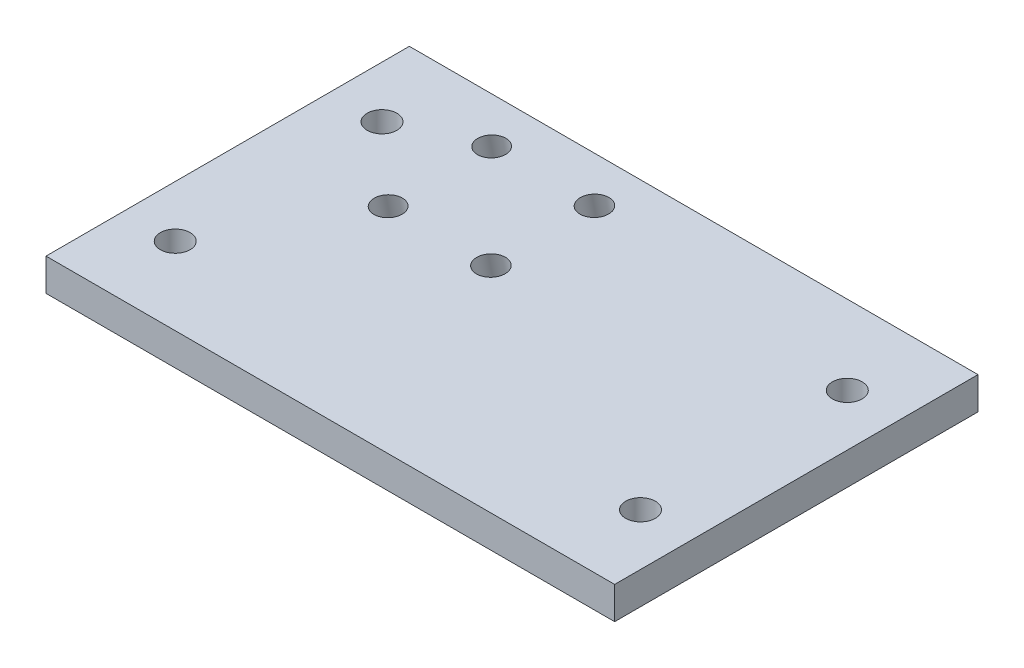
SolidWorks part; units mm, degrees
ref_plane "Front" through (0, 0, 0) normal (0, 0, 1) x (1, 0, 0)
ref_plane "Top" through (0, 0, 0) normal (0, 1, 0) x (1, 0, 0)
ref_plane "Right" through (0, 0, 0) normal (1, 0, 0) x (0, 0, -1)
sketch "Sketch1" plane through (0, 0, 0) normal (0, 1, 0) x (1, 0, 0)
  line L1 (0, 0) -> (90, 0)
  line L2 (0, 0) -> (0, 56.23)
  line L3 (0, 56.23) -> (90, 56.23)
  line L4 (90, 0) -> (90, 56.23)
  dimension "D1" = 90
  dimension "D2" = 56.23
extrude "Boss-Extrude1" add sketch "Sketch1" along normal blind 5
sketch "Sketch2" plane through (0, 5, 0) normal (0, 1, 0) x (1, 0, 0)
  circle A0 centre (82, 12) radius 2.3
  circle A1 centre (10, 12) radius 2.3
extrude "Cut-Extrude1" cut sketch "Sketch2" against normal blind 15
sketch "Sketch4" plane through (0, 5, 0) normal (0, 1, 0) x (1, 0, 0)
  circle A0 centre (39.2121, 27.5705) radius 2.2
  circle A1 centre (23.8176, 32.2728) radius 2.2
  circle A2 centre (43.572, 44.174) radius 2.2
  circle A3 centre (28.1775, 48.8763) radius 2.2
ref_plane "Plane1" through (0, 4.818, 0.9365) normal (0, 0.9816, 0.1908) x (1, 0, 0)
sketch "Sketch6" plane through (0, 4.818, 0.9365) normal (0, 0.9816, 0.1908) x (1, 0, 0)
  circle A0 centre (28.1775, 48.9324) radius 2.0398
  circle A1 centre (23.8176, 32.6339) radius 2.0398
  circle A2 centre (39.2121, 28.018) radius 2.0398
  circle A3 centre (43.572, 44.3165) radius 2.0398
sketch "Sketch7" plane through (0, 5, 0) normal (0, 1, 0) x (1, 0, 0)
  circle A0 centre (82, 44) radius 2.3
  circle A1 centre (10, 44) radius 2.3
extrude "Cut-Extrude3" cut sketch "Sketch7" against normal blind 45
sketch "Sketch8" plane through (0, 0, 0) normal (-1, 0, 0) x (0, 0, 1)
  circle A0 centre (-29.8532, 2.0033) radius 1.2661
sketch "Sketch9" plane through (0, 0, 0) normal (-1, 0, 0) x (0, 0, 1)
  line L1 (-56.23, 0) -> (4.9539, 0)
  line L2 (-56.23, 0) -> (-56.23, 5.0439)
  line L3 (-56.23, 5.0439) -> (4.9539, 5.0439)
  line L4 (4.9539, 0) -> (4.9539, 5.0439)
extrude "Cut-Extrude4" cut sketch "Sketch9" against normal blind 2
sketch "Sketch10" plane through (0, 0, 0) normal (0, -1, 0) x (-1, 0, 0)
  circle A0 centre (-21.7903, 34.1259) radius 2.2
  circle A1 centre (-37.7005, 34.1259) radius 2.2
  circle A2 centre (-21.7903, 50.1487) radius 2.2
  circle A3 centre (-37.7005, 50.1487) radius 2.2
sketch "Sketch11" plane through (0, 4.818, 0.9365) normal (0, 0.9816, 0.1908) x (1, 0, 0)
  circle A0 centre (21.7903, 49.2273) radius 2.1596
  circle A1 centre (37.7005, 49.2273) radius 2.2
  circle A2 centre (37.7005, 33.499) radius 2.2001
  circle A3 centre (21.7903, 33.499) radius 2.1596
extrude "Cut-Extrude5" cut sketch "Sketch11" against normal blind 20
